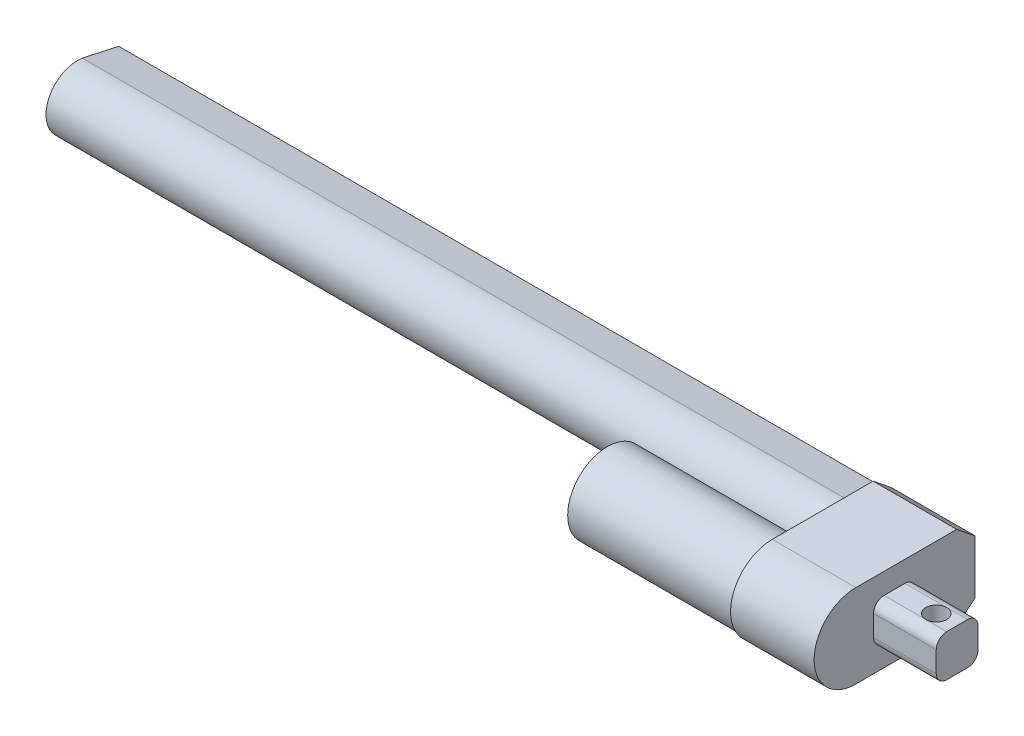
SolidWorks part; units mm, degrees
ref_plane "Alzado" through (0, 0, 0) normal (0, 0, 1) x (1, 0, 0)
ref_plane "Planta" through (0, 0, 0) normal (0, 1, 0) x (1, 0, 0)
ref_plane "Vista lateral" through (0, 0, 0) normal (1, 0, 0) x (0, 0, -1)
sketch "Croquis2" plane through (0, 0, 0) normal (1, 0, 0) x (0, 0, -1)
  line L0 (0, 0) -> (0, -22)
  line L1 (0, -11) -> (-34.8345, -11) construction
  line L2 (0, -11) -> (-17.4172, -11) construction
  line L3 (-17.4172, -11) -> (-17.4172, 3.804) construction
  line L4 (0, 0) -> (-17.4172, 3.804)
  line L5 (0, -22) -> (-17.4172, -25.804)
  line L6 (-34.8345, -11) -> (-29.82, -11) construction
  line L7 (-29.82, -11) -> (-19.82, -11) construction
  circle A2 centre (-19.82, -11) radius 10 construction
  arc A3 (-17.4172, -25.804) -> (-17.4172, 3.804) centre (-19.8345, -11) cw
  dimension "D1" = 11
  dimension "D4" = 10
extrude "Saliente-Extruir2" add sketch "Croquis2" along normal blind 370 contours L4 A3 L5 L0
sketch "Croquis3" plane through (0, 0, 0) normal (-1, 0, 0) x (0, 0, 1)
  circle A0 centre (19.82, -11) radius 10 construction
  circle A1 centre (19.82, -11) radius 10
extrude "Cortar-Extruir1" cut sketch "Croquis3" against normal blind 360
sketch "Croquis4" plane through (370, 0, 0) normal (1, 0, 0) x (0, 0, -1)
  line L0 (0, -11) -> (0, 2)
  line L1 (0, 0) -> (0, -22) construction
  line L2 (-8.7086, 9) -> (-57, 9)
  line L4 (-57, -31) -> (-8.7086, -31)
  line L5 (0, -24) -> (0, -11)
  line L6 (-8.7086, 1.902) -> (-8.7086, 9) construction
  line L7 (0, 0) -> (-17.4172, 3.804) construction
  line L8 (0, 2) -> (-8.7086, 9)
  line L9 (0, -11) -> (-6.7586, -11) construction
  line L10 (0, -24) -> (-8.7086, -31)
  line L11 (-77, -11) -> (-57, -11) construction
  arc A0 (-57, 9) -> (-57, -31) centre (-57, -11) ccw
  dimension "D1" = 20
extrude "Saliente-Extruir3" add sketch "Croquis4" along normal blind 40
sketch "Croquis5" plane through (410, 0, 0) normal (1, 0, 0) x (0, 0, -1)
  line L0 (0, -11) -> (-38.5, -11) construction
  line L1 (0, -24) -> (0, 2) construction
  line L2 (-38.5, -11) -> (-38.5, -1) construction
  line L3 (-38.5, -1) -> (-48.5, -1) construction
  line L4 (-38.5, -11) -> (-38.5, -21) construction
  line L5 (-38.5, -21) -> (-28.5, -21) construction
  line L7 (-43.5, -1) -> (-33.5, -1)
  line L8 (-48.5, -6) -> (-48.5, -16)
  line L9 (-43.5, -21) -> (-33.5, -21)
  line L10 (-28.5, -6) -> (-28.5, -16)
  arc A0 (-28.5, -16) -> (-33.5, -21) centre (-33.5, -16) cw
  arc A1 (-48.5, -16) -> (-43.5, -21) centre (-43.5, -16) ccw
  arc A2 (-48.5, -6) -> (-43.5, -1) centre (-43.5, -6) cw
  arc A3 (-33.5, -1) -> (-28.5, -6) centre (-33.5, -6) cw
  dimension "D4" = 5
  dimension "D1" = 38.5
  dimension "D2" = 10
  dimension "D3" = 10
  dimension "D5" = 10
extrude "Saliente-Extruir4" add sketch "Croquis5" along normal blind 30
sketch "Croquis6" plane through (0, -1, 0) normal (0, 1, 0) x (1, 0, 0)
  line L0 (440, -38.5) -> (430, -38.5) construction
  line L1 (440, -33.5) -> (440, -43.5) construction
  circle A0 centre (430, -38.5) radius 5
  dimension "D1" = 10
extrude "Cortar-Extruir2" cut sketch "Croquis6" against normal up to next
sketch "Croquis7" plane through (370, 0, 0) normal (-1, 0, 0) x (0, 0, 1)
  line L0 (57, -11) -> (57, 9) construction
  line L1 (8.7086, 9) -> (57, 9) construction
  line L2 (77, -11) -> (76, -11) construction
  circle A0 centre (57, -11) radius 19
  arc A2 (57, -31) -> (57, 9) centre (57, -11) ccw construction
  dimension "D1" = 20
  dimension "D2" = 1
  dimension "D4" = 38
extrude "Saliente-Extruir5" add sketch "Croquis7" along normal blind 79
sketch "Croquis8" plane through (0, 0, 0) normal (-1, 0, 0) x (0, 0, 1)
  line L0 (19.82, -11) -> (35.02, -11) construction
  circle A0 centre (19.82, -11) radius 15.2
  dimension "D1" = 15.2
